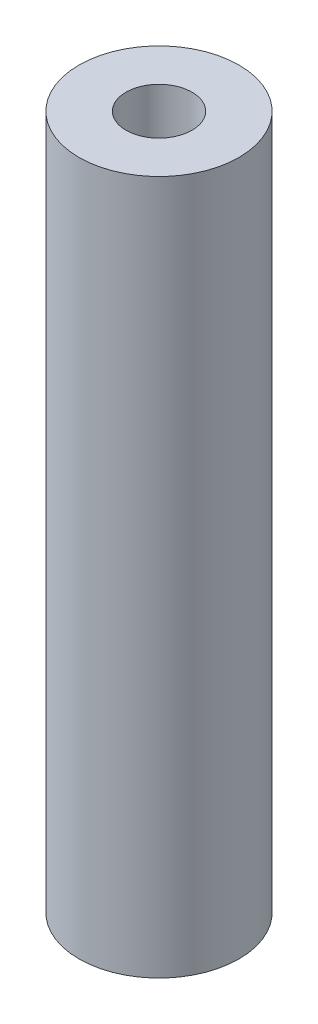
SolidWorks part; units mm, degrees
material "1060 合金"
ref_plane "正面" through (0, 0, 0) normal (0, 0, 1) x (1, 0, 0)
ref_plane "平面" through (0, 0, 0) normal (0, 1, 0) x (1, 0, 0)
ref_plane "右側面" through (0, 0, 0) normal (1, 0, 0) x (0, 0, -1)
sketch "ｽｹｯﾁ1" plane through (0, 0, 0) normal (0, 1, 0) x (1, 0, 0)
  circle A0 centre (0, 0) radius 4
  dimension "D1" = 8
extrude "ﾎﾞｽ - 押し出し1" add sketch "ｽｹｯﾁ1" along normal blind 34.7
sketch "ｽｹｯﾁ2" plane through (0, 34.7, 0) normal (0, 1, 0) x (1, 0, 0)
  circle A0 centre (0, 0) radius 1.65
  dimension "D1" = 3.3
extrude "ｶｯﾄ - 押し出し1" cut sketch "ｽｹｯﾁ2" against normal blind 12
sketch "ｽｹｯﾁ3" plane through (0, 0, 0) normal (0, -1, 0) x (1, 0, 0)
  circle A0 centre (0, 0) radius 1.65
  dimension "D1" = 3.3
extrude "ｶｯﾄ - 押し出し2" cut sketch "ｽｹｯﾁ3" against normal blind 12
